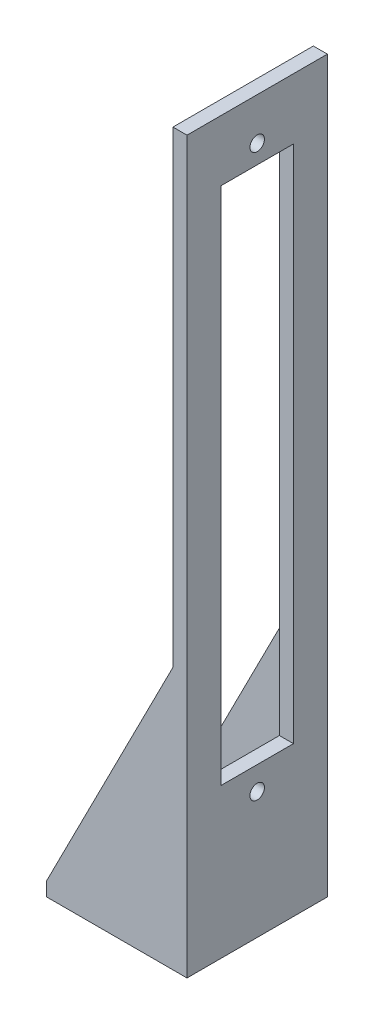
SolidWorks part; units mm, degrees
ref_plane "Plano frontal" through (0, 0, 0) normal (0, 0, 1) x (1, 0, 0)
ref_plane "Plano superior" through (0, 0, 0) normal (0, 1, 0) x (1, 0, 0)
ref_plane "Plano direito" through (0, 0, 0) normal (1, 0, 0) x (0, 0, -1)
sketch "Esboço1" plane through (0, 0, 0) normal (0, 1, 0) x (1, 0, 0)
  line L1 (-15, -15) -> (15, -15)
  line L2 (-15, -15) -> (-15, 15)
  line L3 (-15, 15) -> (15, 15)
  line L4 (15, -15) -> (15, 15)
  line L5 (-15, -15) -> (15, 15) construction
  line L6 (-15, 15) -> (15, -15) construction
  circle A0 centre (-9, -7) radius 1.55
  circle A2 centre (7, 9) radius 1.55
  point P0 (0, 0)
  dimension "D7" = 3.1
  dimension "D8" = 3.1
  dimension "D1" = 30
  dimension "D2" = 30
  dimension "D3" = 6
  dimension "D4" = 8
  dimension "D5" = 22
  dimension "D6" = 24
extrude "Ressalto-extrusão1" add sketch "Esboço1" along normal blind 3
sketch "Esboço2" plane through (0, 3, 0) normal (0, 1, 0) x (1, 0, 0)
  line L0 (-15, -15) -> (15, -15) construction
  line L1 (15, 15) -> (12, 15)
  line L2 (15, 15) -> (15, -15)
  line L3 (15, -15) -> (12, -15)
  line L4 (12, 15) -> (12, -15)
  dimension "D1" = 3
extrude "Ressalto-extrusão2" add sketch "Esboço2" along normal blind 153
sketch "Esboço3" plane through (15, 0, 0) normal (1, 0, 0) x (0, 0, -1)
  line L0 (-15, 156) -> (15, 156) construction
  line L1 (-15, 156) -> (-15, 0) construction
  line L2 (15, 156) -> (15, 0) construction
  line L5 (-7.75, 32) -> (7.75, 32)
  line L6 (-7.75, 32) -> (-7.75, 143)
  line L7 (-7.75, 143) -> (7.75, 143)
  line L8 (7.75, 32) -> (7.75, 143)
  line L9 (-7.75, 32) -> (7.75, 143) construction
  line L10 (-7.75, 143) -> (7.75, 32) construction
  circle A0 centre (0, 147) radius 1.55
  circle A1 centre (0, 27) radius 1.55
  point P12 (0, 87.5)
  dimension "D1" = 3.1
  dimension "D2" = 3.1
  dimension "D5" = 15
  dimension "D6" = 120
  dimension "D3" = 9
  dimension "D4" = 15
  dimension "D7" = 15
  dimension "D8" = 13
  dimension "D9" = 15.5
  dimension "D10" = 111
extrude "Corte-extrusão1" cut sketch "Esboço3" against normal blind 153
sketch "Esboço4" plane through (0, 0, 15) normal (0, 0, 1) x (1, 0, 0)
  line L0 (12, 56) -> (-15, 3)
  line L1 (12, 156) -> (12, 3) construction
  line L2 (-15, 3) -> (12, 3)
  line L3 (12, 3) -> (12, 56)
  line L4 (12, 156) -> (15, 156) construction
  dimension "D1" = 100
extrude "Ressalto-extrusão3" add sketch "Esboço4" against normal blind 3
sketch "Esboço5" plane through (0, 0, -15) normal (0, 0, -1) x (-1, 0, 0)
  line L0 (15, 3) -> (-12, 56)
  line L1 (-12, 56) -> (-12, 3)
  line L2 (-12, 3) -> (15, 3)
extrude "Ressalto-extrusão4" add sketch "Esboço5" against normal blind 3
